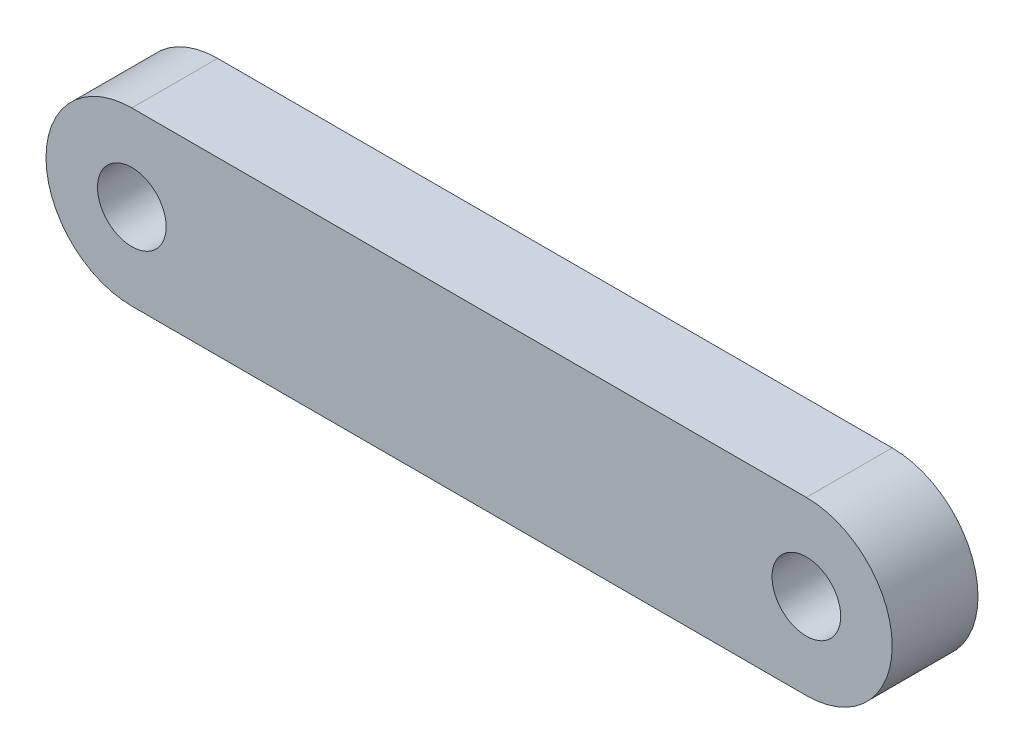
SolidWorks part; units mm, degrees
ref_plane "前基準面" through (0, 0, 0) normal (0, 0, 1) x (1, 0, 0)
ref_plane "上基準面" through (0, 0, 0) normal (0, 1, 0) x (1, 0, 0)
ref_plane "右基準面" through (0, 0, 0) normal (1, 0, 0) x (0, 0, -1)
sketch "草圖2" plane through (0, 0, 0) normal (0, 0, 1) x (1, 0, 0)
  line L0 (-19.65, 0) -> (19.65, 0) construction
  line L1 (-19.65, 5) -> (19.65, 5)
  line L2 (-19.65, -5) -> (19.65, -5)
  arc A0 (-19.65, 5) -> (-19.65, -5) centre (-19.65, 0) ccw
  arc A1 (19.65, -5) -> (19.65, 5) centre (19.65, 0) ccw
  circle A2 centre (19.65, 0) radius 2
  circle A3 centre (-19.65, 0) radius 2
  point P2 (0, 0)
  dimension "D2" = 4
  dimension "D3" = 5
  dimension "D1" = 39.3
extrude "填料-伸長1" add sketch "草圖2" along normal mid plane 5
